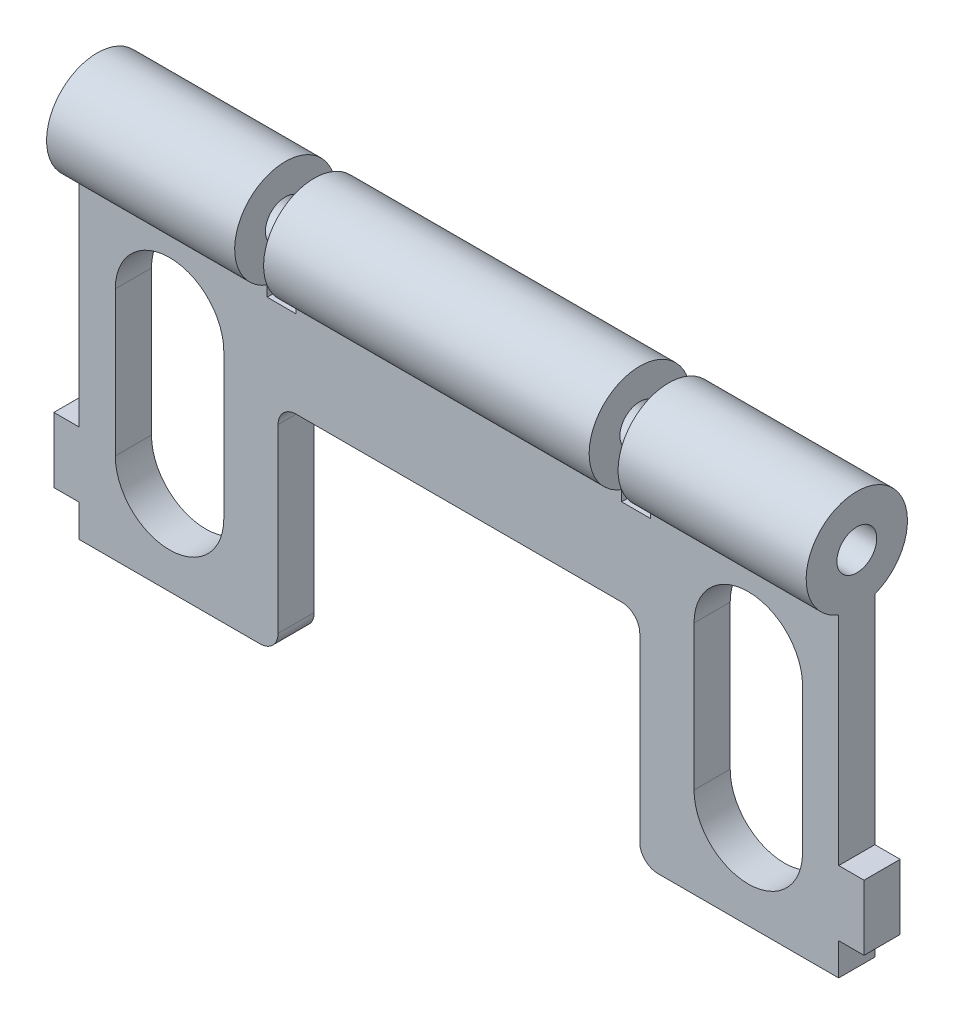
SolidWorks part; units mm, degrees
ref_plane "Front Plane" through (0, 0, 0) normal (0, 0, 1) x (1, 0, 0)
ref_plane "Top Plane" through (0, 0, 0) normal (0, 1, 0) x (1, 0, 0)
ref_plane "Right Plane" through (0, 0, 0) normal (1, 0, 0) x (0, 0, -1)
sketch "Sketch1" plane through (0, 0, 0) normal (1, 0, 0) x (0, 0, -1)
  line L1 (-0.5, 5) -> (0.5, 5)
  line L2 (-0.5, 5) -> (-0.5, -5)
  line L3 (-0.5, -5) -> (0.5, -5)
  line L4 (0.5, 5) -> (0.5, -5)
  line L5 (-0.5, 5) -> (0.5, -5) construction
  line L6 (-0.5, -5) -> (0.5, 5) construction
  circle A0 centre (0, 5) radius 1.4
  point P0 (0, 0)
  dimension "D3" = 2.8
  dimension "D1" = 1
  dimension "D2" = 10
extrude "Boss-Extrude1" add sketch "Sketch1" along normal mid plane 21 contours L4 A0 L2 L1 | A0 L2 L3 L4 | L2 A0 L4 L1
sketch "Sketch2" plane through (0, 0, 0.5) normal (0, 0, 1) x (1, 0, 0)
  line L0 (10.5, -5) -> (-10.5, -5) construction
  line L1 (-5, -5) -> (5, -5)
  line L2 (-5, -5) -> (-5, 1)
  line L3 (-5, 1) -> (5, 1)
  line L4 (5, -5) -> (5, 1)
  line L5 (10.5, 6.4) -> (-10.5, 6.4) construction
  line L6 (-5.3, 6.4) -> (-4.5, 6.4)
  line L7 (-5.3, 6.4) -> (-5.3, 3.4)
  line L8 (-5.3, 3.4) -> (-4.5, 3.4)
  line L9 (-4.5, 6.4) -> (-4.5, 3.4)
  line L10 (-8, 1.5) -> (-8, -2.5) construction
  line L11 (-6.5, 1.5) -> (-6.5, -2.5)
  line L12 (-9.5, 1.5) -> (-9.5, -2.5)
  line L13 (0, 8.4568) -> (0, -8.8277) construction
  line L14 (8, 1.5) -> (8, -2.5) construction
  line L15 (6.5, 1.5) -> (6.5, -2.5)
  line L16 (9.5, 1.5) -> (9.5, -2.5)
  line L17 (5.3, 3.4) -> (4.5, 3.4)
  line L18 (5.3, 6.4) -> (5.3, 3.4)
  line L19 (4.5, 6.4) -> (4.5, 3.4)
  line L20 (5.3, 6.4) -> (4.5, 6.4)
  arc A0 (-6.5, 1.5) -> (-9.5, 1.5) centre (-8, 1.5) ccw
  arc A1 (-9.5, -2.5) -> (-6.5, -2.5) centre (-8, -2.5) ccw
  arc A2 (6.5, 1.5) -> (9.5, 1.5) centre (8, 1.5) cw
  arc A3 (9.5, -2.5) -> (6.5, -2.5) centre (8, -2.5) cw
  point P15 (-8, -0.5)
  point P24 (8, -0.5)
  dimension "D9" = 1.5
  dimension "D1" = 6
  dimension "D2" = 10
  dimension "D3" = 5
  dimension "D4" = 0.8
  dimension "D5" = 3
  dimension "D6" = 4.5
  dimension "D7" = 4
  dimension "D8" = 2.5
  dimension "D10" = 8
extrude "Cut-Extrude1" cut sketch "Sketch2" against normal mid plane 21
hole_wizard "M1.4x0.3 Tapped Hole1" positions "3DSketch1" profile "Sketch3" tap size "M1.4x0.3" standard "ANSI Metric" end condition through all
sketch3d "3DSketch1"
  line L0 (10.5, 5, 0) -> (5.3, 5, 0) construction
  point P0 (10.5, 5, 0)
sketch "Sketch3" plane through (10.5, 5, 0) normal (0, 1, 0) x (0, 0, -1)
  line L0 (0, 0) -> (0, 21)
  line L1 (0, 21) -> (0.55, 21)
  line L2 (0.55, 21) -> (0.55, 0)
  line L5 (0.55, 0) -> (0, 0)
  line L11 (0, -6.35) -> (0, 107.95) construction
  dimension "Thru Tap Drill Dia." = 1.1
  dimension "Thru Tap Drill Depth" = 21
cosmetic thread "Hole Thread1" parameters "D2"=1.4
sketch "Sketch4" plane through (0, 0, 0) normal (0, 0, 1) x (1, 0, 0)
  line L0 (10.5, 3.6923) -> (10.5, -5) construction
  line L1 (10.5, -2.3077) -> (11.2, -2.3077)
  line L2 (10.5, -2.3077) -> (10.5, -4.1077)
  line L3 (10.5, -4.1077) -> (11.2, -4.1077)
  line L4 (11.2, -2.3077) -> (11.2, -4.1077)
  line L5 (10.5, 3.6923) -> (5.3, 3.6923) construction
  dimension "D1" = 1.8
  dimension "D2" = 0.7
  dimension "D3" = 6
extrude "Boss-Extrude2" add sketch "Sketch4" along normal mid plane 1
mirror "Mirror1" about plane through (0, 0, 0) normal (1, 0, 0) of "Boss-Extrude2"
fillet "Fillet1" radius 0.5 4 edges at (-5, 1, 0) (-5, -5, 0) (5, -5, 0) (5, 1, 0)
